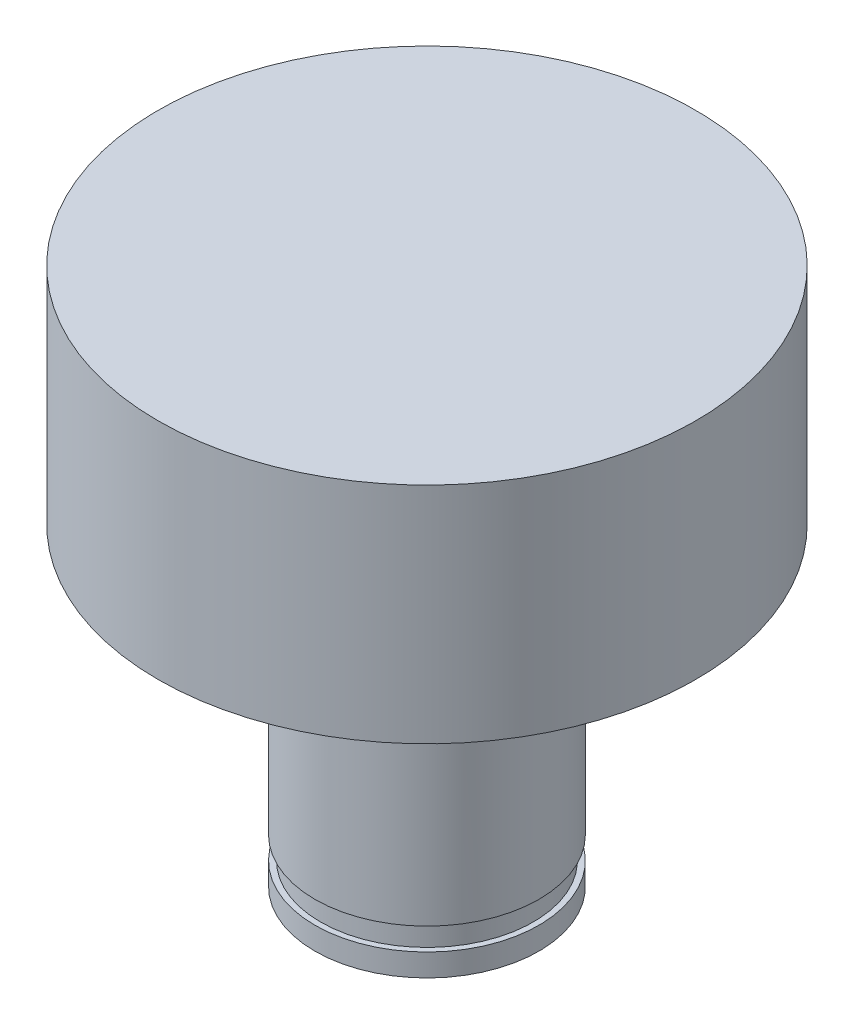
SolidWorks part; units mm, degrees
ref_plane "Front Plane" through (0, 0, 0) normal (0, 0, 1) x (1, 0, 0)
ref_plane "Top Plane" through (0, 0, 0) normal (0, 1, 0) x (1, 0, 0)
ref_plane "Right Plane" through (0, 0, 0) normal (1, 0, 0) x (0, 0, -1)
sketch "Sketch1" plane through (0, 0, 0) normal (0, 1, 0) x (1, 0, 0)
  circle A0 centre (0, 0) radius 6
  dimension "D1" = 12
extrude "Boss-Extrude1" add sketch "Sketch1" along normal blind 5
sketch "Sketch2" plane through (0, 5, 0) normal (0, 1, 0) x (-1, 0, 0)
  circle A0 centre (0, 0) radius 2.5
  dimension "D1" = 5
extrude "Boss-Extrude2" add sketch "Sketch2" against normal blind 12
ref_plane "Plane1" through (0, -7, 0) normal (-1, 0, 0) x (0, 0, 1)
sketch "Sketch4" plane through (0, -7, 0) normal (-1, 0, 0) x (0, 0, 1)
  line L0 (2.375, 0.5017) -> (3, 0.5017)
  line L1 (3, 0.5017) -> (3, 1.0017)
  line L2 (3, 1.0017) -> (2.375, 1.0017)
  line L3 (2.375, 1.0017) -> (2.375, 0.5017)
  line L4 (0, -50) -> (0, 50) construction
revolve "Groove for ANSI B27.7 - 3AM1-5, Basic External Retaining Ring1" cut sketch "Sketch4"
